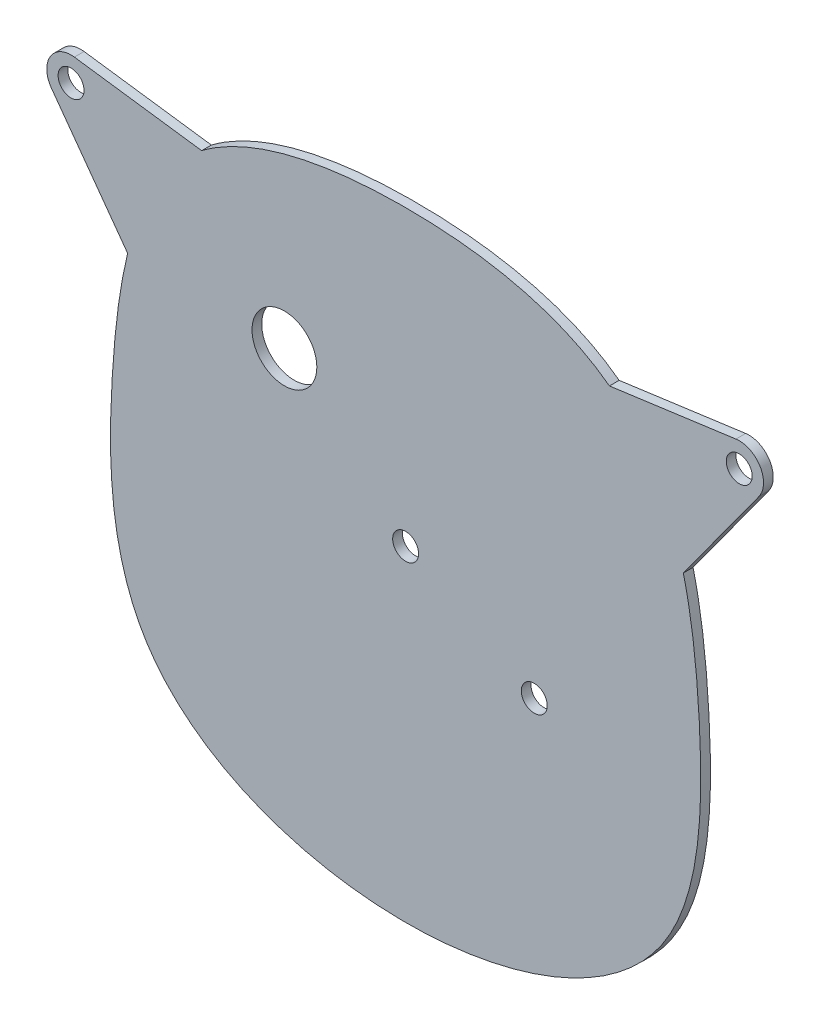
SolidWorks part; units mm, degrees
ref_plane "前视基准面" through (0, 0, 0) normal (0, 0, 1) x (1, 0, 0)
ref_plane "上视基准面" through (0, 0, 0) normal (0, 1, 0) x (1, 0, 0)
ref_plane "右视基准面" through (0, 0, 0) normal (1, 0, 0) x (0, 0, -1)
sketch "草图1" plane through (0, 0, 0) normal (0, 0, 1) x (1, 0, 0)
  line L2 (0, 53) -> (2.5, 53.3413)
  line L3 (0, -95.026) -> (0, -98) construction
  line L5 (101.758, 58.75) -> (104.3561, 60.25) construction
  line L6 (-101.758, 58.75) -> (-104.3561, 60.25) construction
  line L9 (-103.057, 59.5) -> (-101.758, 58.75) construction
  line L10 (101.758, 58.75) -> (103.057, 59.5) construction
  line L13 (0, -95.026) -> (0, -98) construction
  line L20 (39.8343, -33.425) -> (37.6262, -36.7603) construction
  line L21 (0, 53) -> (-102.0425, 66.9311)
  line L22 (-109.1235, 55.0901) -> (0, -95.026)
  line L59 (36.7701, -30.8538) -> (42.9059, -36.0023) construction
  line L63 (109.1235, 55.0901) -> (0, -95.026)
  line L70 (2.5, 53.3413) -> (102.0425, 66.9311)
  arc A2 (74.6555, 7.1799) -> (74.4943, 8.695) centre (0, 0) ccw
  circle A3 centre (39.8343, -33.425) radius 4
  arc A6 (-102.0425, 66.9311) -> (-109.1235, 55.0901) centre (-103.057, 59.5) ccw
  circle A7 centre (-103.057, 59.5) radius 1.5
  circle A9 centre (103.057, 59.5) radius 1.5
  circle A11 centre (-37.2391, 21.5) radius 10
  arc A13 (109.1235, 55.0901) -> (102.0425, 66.9311) centre (103.057, 59.5) ccw
  point P3 (33.0244, 57.7315)
  point P15 (-39.8343, -33.425)
  point P29 (88, 0)
  point P30 (-88, 0)
  point P36 (-67.1751, 67.1751)
  point P37 (67.1751, 67.1751)
  point P42 (77.3705, -64.9215)
  point P46 (-77.3705, -64.9215)
  point P48 (35.5216, 57.8495)
  point P52 (-9, -80)
  point P53 (9, -80)
  point P54 (9, -97.696)
  point P55 (0, 53)
  point P56 (-9, -97.696)
  point P57 (0, 53)
  point P63 (-104.3313, 58.7018)
  point P64 (-38.3426, -32.0756)
  point P65 (-104.307, 57.3349)
  point P66 (-38.4891, 19.3349)
  point P67 (0.6763, 48.046)
  point P68 (-1.25, -2.1651)
  point P69 (-101.807, 61.6651)
  point P70 (-35.9891, 23.6651)
  point P72 (1.25, 2.1651)
  point P73 (0, 50.5)
  point P74 (-72.6921, -6.1091)
  point P75 (-38.7751, 23.4724)
  point P76 (-74.2282, -4.1367)
  point P77 (-1.536, 52.4724)
  point P78 (-34.7419, 21.382)
  point P79 (-35.703, 19.5276)
  point P80 (-71.1561, -8.0816)
  point P81 (1.536, 48.5276)
  point P82 (-37.3371, -33.5429)
  point P83 (-33.1399, 55.2855)
  point P84 (-35.6371, 55.4035)
  point P85 (-39.7363, 21.618)
  point P86 (-42.3315, -33.307)
  point P87 (-38.1344, 55.5215)
  point P88 (-41.9189, -34.805)
  point P89 (-11.0846, -81.3801)
  point P90 (-37.7497, -32.0449)
  point P91 (-6.9154, -78.6199)
  point P92 (37.7497, -32.0449)
  point P93 (6.9154, -78.6199)
  point P94 (41.9189, -34.805)
  point P95 (11.0846, -81.3801)
  point P96 (11, -78)
  point P97 (11, -97.696)
  point P98 (-11, -78)
  point P99 (-11, -97.696)
  point P100 (7, -82)
  point P101 (7, -97.696)
  point P102 (-7, -82)
  point P103 (-7, -97.696)
  point P104 (-2.5, 88)
  point P105 (-2.5, -98)
  point P106 (2.5, 88)
  point P107 (2.5, -98)
  point P108 (-39.8343, -35.925)
  point P109 (39.8343, -35.925)
  point P110 (-39.8343, -30.925)
  point P111 (39.8343, -30.925)
  point P112 (-1.607, 1.9151)
  point P113 (-78.9775, -63.0064)
  point P114 (1.607, -1.9151)
  point P115 (-75.7635, -66.8367)
  point P116 (-1.607, -1.9151)
  point P117 (75.7635, -66.8367)
  point P118 (1.607, 1.9151)
  point P119 (78.9775, -63.0064)
  point P123 (43.0933, -35.7445)
  point P124 (105.0792, 58.03)
  point P125 (39.049, -32.8046)
  point P126 (82.97, -14.113)
  point P127 (-1.536, 48.5276)
  point P128 (81.434, -16.0855)
  point P129 (1.536, 52.4724)
  point P130 (84.5061, -12.1406)
  point P131 (103.1748, 62.0393)
  point P134 (102.4985, 66.9933)
  point P135 (1.25, -2.1651)
  point P136 (104.307, 57.3349)
  point P137 (-1.25, 2.1651)
  point P138 (101.807, 61.6651)
  point P155 (6.2441, 48.8061)
  point P196 (37.3371, -33.5429)
  point P197 (38.0188, 57.9675)
  point P198 (42.3315, -33.307)
  dimension "D23" = 3
sketch "草图2" plane through (0, 0, 0) normal (0, 0, 1) x (1, 0, 0)
  line L6 (-62.9217, 74.2458) -> (-102.191, 79.6069)
  line L7 (-109.272, 67.7659) -> (-85.7485, 35.4058)
  line L9 (108.9751, 67.7659) -> (85.6736, 35.7112)
  line L10 (62.8762, 74.2801) -> (101.8941, 79.6069)
  circle A0 centre (0, 0) radius 4
  circle A1 centre (39.6859, -20.7491) radius 4
  arc A2 (-102.191, 79.6069) -> (-109.272, 67.7659) centre (-103.2055, 72.1759) ccw
  circle A3 centre (-103.2055, 72.1759) radius 4
  circle A4 centre (102.9086, 72.1759) radius 4
  circle A5 centre (-37.3875, 34.1759) radius 10
  arc A6 (108.9751, 67.7659) -> (101.8941, 79.6069) centre (102.9086, 72.1759) ccw
  spline S0 degree 3 poles (85.6736, 35.7112) (85.777, 35.2922) (87.3831, 28.633) (89.0072, 18.401) (90.214, 5.0524) (91.0234, -8.3002) (91.2491, -24.8803) (89.4828, -40.6689) (86.3144, -52.4437) (82.9151, -60.7387) (78.3185, -68.3854) (70.5643, -77.4788) (58.292, -86.7783) (40.5306, -94.6999) (20.7665, -99.4438) (0, -101.0281) (-20.7665, -99.4438) (-40.5306, -94.6999) (-58.292, -86.7783) (-70.5643, -77.4788) (-78.3185, -68.3854) (-82.9151, -60.7387) (-86.3144, -52.4437) (-89.4828, -40.6689) (-91.2491, -24.8803) (-91.0234, -8.3002) (-90.214, 5.0524) (-89.0072, 18.401) (-87.4, 28.5262) (-85.8261, 35.0881) (-85.7485, 35.4058) knots 1.185395 1.185395 1.185395 1.185395 1.1875 1.21875 1.234375 1.25 1.28125 1.3125 1.328125 1.34375 1.359375 1.375 1.40625 1.4375 1.46875 1.5 1.53125 1.5625 1.59375 1.625 1.640625 1.65625 1.671875 1.6875 1.71875 1.75 1.765625 1.78125 1.8125 1.814094 1.814094 1.814094 1.814094
  spline S2 degree 3 poles (-62.9217, 74.2458) (-60.945, 75.7387) (-53.8533, 80.3839) (-39.8914, 86.0514) (-20.4499, 89.7926) (-6.8166, 90.5) (0, 90.5) (6.8166, 90.5) (20.4499, 89.7926) (39.8914, 86.0514) (53.8348, 80.3914) (60.913, 75.7597) (62.8762, 74.2801) knots 0.89321 0.89321 0.89321 0.89321 0.90625 0.9375 0.96875 1 1 1 1.03125 1.0625 1.09375 1.10669 1.10669 1.10669 1.10669
  dimension "D3" = 8
  dimension "D2" = 8
  dimension "D4" = 8
  dimension "D1" = 206.114
extrude "凸台-拉伸2" add sketch "草图2" along normal blind 3
